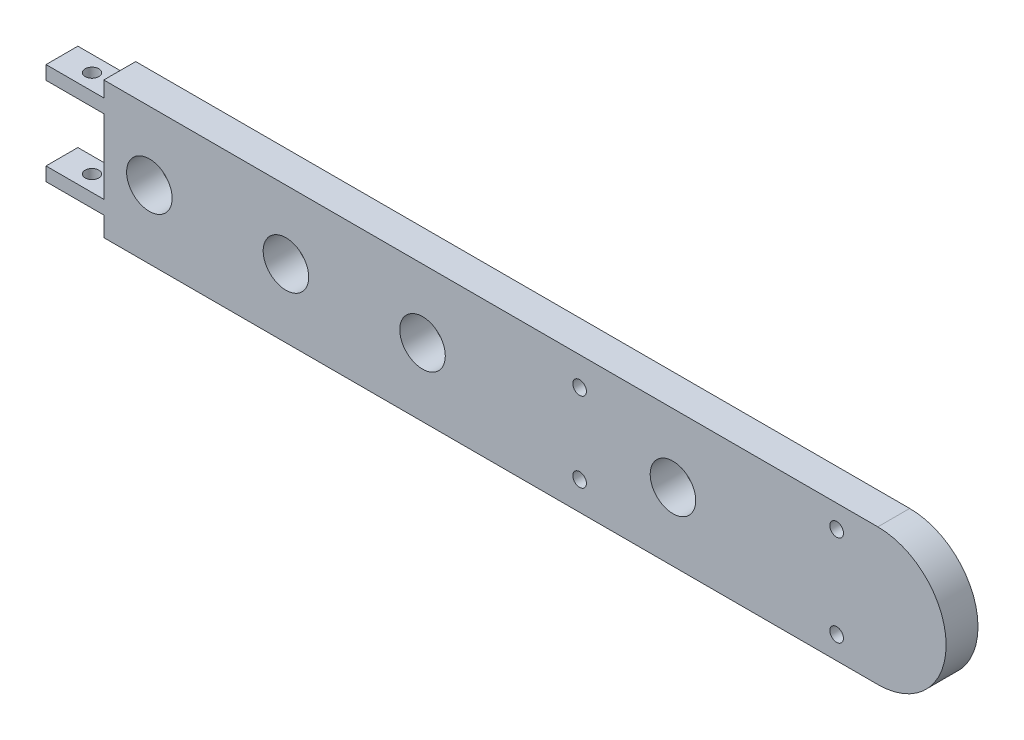
SolidWorks part; units mm, degrees
ref_plane "Front Plane" through (0, 0, 0) normal (0, 0, 1) x (1, 0, 0)
ref_plane "Top Plane" through (0, 0, 0) normal (0, 1, 0) x (1, 0, 0)
ref_plane "Right Plane" through (0, 0, 0) normal (1, 0, 0) x (0, 0, -1)
sketch "Sketch1" plane through (0, 0, 0) normal (0, 0, 1) x (1, 0, 0)
  line L0 (-200, 0) -> (50, 0)
  line L1 (50, -30) -> (-200, -30)
  arc A0 (50, 0) -> (50, -30) centre (50, -15) cw
  arc A1 (-200, -30) -> (-200, 0) centre (-200, -15) cw
  point P7 (-75, 0)
  dimension "D3" = 50
  dimension "D1" = 125
  dimension "D2" = 30
extrude "Boss-Extrude1" add sketch "Sketch1" along normal blind 7
sketch "Sketch2" plane through (0, 0, 7) normal (0, 0, 1) x (1, 0, 0)
  line L2 (50, 0) -> (-200, 0) construction
  circle A0 centre (-185, -15) radius 5
  arc A6 (-200, 0) -> (-200, -30) centre (-200, -15) ccw construction
  point P22 (-215, -15)
  dimension "D1" = 10
  dimension "D3" = 15
  dimension "D2" = 30
extrude "Cut-Extrude1" cut sketch "Sketch2" against normal blind 7
sketch "Sketch5" plane through (0, 0, 0) normal (0, 1, 0) x (1, 0, 0)
  line L1 (-318.748, 64.8797) -> (45.4135, 64.8797) construction
  line L2 (-318.748, 64.8797) -> (-318.748, -30.5338) construction
  line L3 (-318.748, -30.5338) -> (45.4135, -30.5338) construction
  line L4 (45.4135, 64.8797) -> (45.4135, -30.5338) construction
  line L5 (-318.748, 64.8797) -> (45.4135, -30.5338) construction
  line L6 (-318.748, -30.5338) -> (45.4135, 64.8797) construction
  point P0 (-136.6672, 17.1729)
pattern_linear "LPattern1" count 7 spacing 30 along (1, 0, 0) of "Cut-Extrude1"
sketch "Sketch6" plane through (0, 0, 0) normal (0, 0, -1) x (-1, 0, 0)
  circle A0 centre (-50, -15) radius 5
  dimension "D1" = 10
extrude "Cut-Extrude2" cut sketch "Sketch6" against normal blind 10
sketch "Sketch9" plane through (0, 0, 0) normal (0, 0, -1) x (-1, 0, 0)
  line L0 (-50, -15) -> (-29.5, -15)
  line L1 (-29.5, -6.25) -> (-29.5, -23.75)
  circle A0 centre (-29.5, -6.25) radius 1.5
  circle A1 centre (-29.5, -23.75) radius 1.5
  point P6 (-29.5, -15)
  dimension "D3" = 3
  dimension "D4" = 3
  dimension "D1" = 20.5
  dimension "D2" = 17.5
extrude "Cut-Extrude4" cut sketch "Sketch9" against normal up to next contours A1 | A0
sketch "Sketch16" plane through (0, 0, 0) normal (0, 0, -1) x (-1, 0, 0)
  line L0 (152.5436, -46.9176) -> (161.1481, -46.9176) construction
  line L1 (133, -51.6913) -> (180, -51.6913)
  line L2 (133, -51.6913) -> (133, -11.7609)
  line L3 (133, -11.7609) -> (180, -11.7609)
  line L4 (180, -51.6913) -> (180, -11.7609)
  line L9 (152.5436, -45.1752) -> (161.1481, -45.1752)
  line L10 (152.5436, -48.6599) -> (161.1481, -48.6599)
  circle A0 centre (143.6458, -39.2434) radius 8.2
  circle A1 centre (169.8064, -39.2434) radius 8.2
  arc A2 (152.5436, -45.1752) -> (152.5436, -48.6599) centre (152.5436, -46.9176) ccw
  arc A3 (161.1481, -48.6599) -> (161.1481, -45.1752) centre (161.1481, -46.9176) ccw
  circle A4 centre (-50, -15) radius 5 construction
  point P17 (156.8458, -46.9176)
  dimension "D3" = 16.4
  dimension "D4" = 16.4
  dimension "D9" = 10.6458
  dimension "D6" = 8.8978
  dimension "D1" = 47
  dimension "D2" = 26.1606
  dimension "D5" = 8.6044
  dimension "D7" = 10.6458
  dimension "D8" = 11.75
  dimension "D10" = 183
extrude "Boss-Extrude2" add sketch "Sketch16" along normal blind 10
sketch "Sketch17" plane through (0, 0, -10) normal (0, 0, -1) x (-1, 0, 0)
  line L0 (133.75, -20.9008) -> (179.5838, -20.9008)
  line L1 (133.75, -20.9008) -> (133.75, -51.0259)
  line L2 (133.75, -51.0259) -> (179.5838, -51.0259)
  line L3 (179.5838, -20.9008) -> (179.5838, -51.0259)
  line L4 (149.9449, -11.7609) -> (163.7082, -11.7609)
  line L5 (149.9449, -11.7609) -> (149.9449, -20.9835)
  line L6 (149.9449, -20.9835) -> (163.7082, -20.9835)
  line L7 (163.7082, -11.7609) -> (163.7082, -20.9835)
  line L8 (133, -11.7609) -> (180, -11.7609) construction
  circle A0 centre (-50, -15) radius 5 construction
  dimension "D1" = 45.8338
  dimension "D2" = 13.7633
  dimension "D3" = 45.8338
  dimension "D4" = 30.1251
  dimension "D5" = 0
  dimension "D6" = 183.75
  dimension "D7" = 16.1949
extrude "Cut-Extrude15" cut sketch "Sketch17" against normal blind 9 contours L0 L3 L2 L1 | L4 L7 L6 L5
sketch "Sketch18" plane through (0, 0, 7) normal (0, 0, 1) x (1, 0, 0)
  line L1 (-75, 42.9164) -> (-215, 42.9164)
  line L2 (-75, 42.9164) -> (-75, -72.9164)
  line L3 (-75, -72.9164) -> (-215, -72.9164)
  line L4 (-215, 42.9164) -> (-215, -72.9164)
  arc A0 (-200, 0) -> (-200, -30) centre (-200, -15) ccw construction
  point P7 (-215, -15)
  point P8 (-215, -15)
  dimension "D1" = 140
extrude "Cut-Extrude18" cut sketch "Sketch18" against normal up to next
ref_plane "Plane1" through (0, 0, 3.5) normal (0, 0, 1) x (1, 0, 0)
sketch "Sketch23" plane through (0, 0, 7) normal (0, 0, 1) x (1, 0, 0)
  line L1 (50, 0) -> (95, 0)
  line L2 (50, 0) -> (50, -30)
  line L3 (50, -30) -> (95, -30)
  line L4 (95, 0) -> (95, -30)
  arc A0 (95, 0) -> (95, -30) centre (95, -15) cw
  circle M7 centre (50, -15) radius 5
  arc M14 (50, -30) -> (50, 0) centre (50, -15) ccw
  dimension "D1" = 45
extrude "Boss-Extrude5" add sketch "Sketch23" against normal blind 7 contours L4 L1 L3 M14 | A0 L4 | L2 M14 M7
sketch "Sketch24" plane through (0, 0, 7) normal (0, 0, 1) x (1, 0, 0)
  line L0 (85.95, 0) -> (85.95, -30)
  line L1 (-75, -30) -> (95, -30) construction
  circle A0 centre (85.95, -25) radius 1.5
  circle A1 centre (85.95, -5) radius 1.5
  arc A2 (95, -30) -> (95, 0) centre (95, -15) ccw construction
  point P9 (110, -15)
  point P10 (85.95, -30)
  dimension "D3" = 3
  dimension "D4" = 3
  dimension "D1" = 30
  dimension "D2" = 20
  dimension "D5" = 5
  dimension "D6" = 24.05
extrude "Cut-Extrude19" cut sketch "Sketch24" against normal blind 10 contours L0 A0 | L0 A0 | L0 A1 | L0 A1
sketch "Sketch25" plane through (-75, 0, 0) normal (-1, 0, 0) x (0, 0, 1)
  line L0 (0, -3.42) -> (7, -3.42)
  line L1 (0, -3.42) -> (0, -6.42)
  line L2 (0, -6.42) -> (7, -6.42)
  line L3 (7, -3.42) -> (7, -6.42)
  line L4 (0, -22.7) -> (7, -22.7)
  line L5 (0, -22.7) -> (0, -25.7)
  line L6 (0, -25.7) -> (7, -25.7)
  line L7 (7, -22.7) -> (7, -25.7)
  line L8 (0, -30) -> (7, -30) construction
  line L9 (0, -30) -> (0, 0) construction
  line L10 (7, -30) -> (7, 0) construction
  dimension "D1" = 16.28
  dimension "D2" = 7
  dimension "D3" = 7
  dimension "D4" = 3
  dimension "D5" = 4.3
  dimension "D6" = 3
extrude "Boss-Extrude6" add sketch "Sketch25" along normal blind 12.7
sketch "Sketch26" plane through (0, -3.42, 0) normal (0, 1, 0) x (1, 0, 0)
  line L0 (-16.5, -3.5) -> (16.5, -3.5) construction
  line L1 (-87.7, -7) -> (-87.7, 0) construction
  circle A0 centre (-81.1, -3.5) radius 1.5
  dimension "D1" = 3
  dimension "D2" = 6.6
extrude "Cut-Extrude20" cut sketch "Sketch26" against normal through all both and the other way through all
